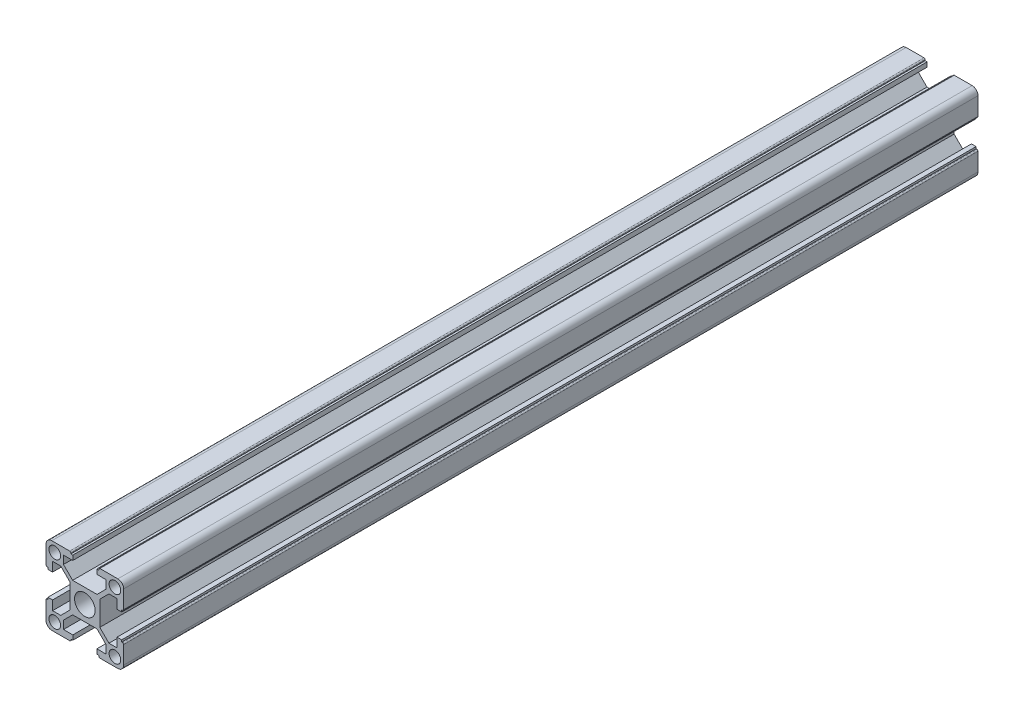
SolidWorks part; units mm, degrees
ref_plane "前视基准面" through (0, 0, 0) normal (0, 0, 1) x (1, 0, 0)
ref_plane "上视基准面" through (0, 0, 0) normal (0, 1, 0) x (1, 0, 0)
ref_plane "右视基准面" through (0, 0, 0) normal (1, 0, 0) x (0, 0, -1)
sketch "草图1" plane through (0, 0, 0) normal (0, 0, 1) x (1, 0, 0)
  line L0 (-7.75, 0) -> (0, 0) construction
  line L1 (7.75, -7.75) -> (-7.75, -7.75) construction
  line L2 (7.75, -7.75) -> (7.75, 7.75) construction
  line L3 (7.75, 7.75) -> (-7.75, 7.75) construction
  line L4 (-7.75, -7.75) -> (-7.75, 7.75) construction
  line L5 (7.75, -7.75) -> (-7.75, 7.75) construction
  line L6 (7.75, 7.75) -> (-7.75, -7.75) construction
  line L7 (0, 0) -> (0, 7.75) construction
  line L8 (3.1429, 3.85) -> (-3.1429, 3.85)
  line L9 (-3.1429, 3.85) -> (-5.5, 6.2071)
  line L10 (-5.5, 6.2071) -> (-5.5, 8.3)
  line L11 (-5.5, 8.3) -> (-3.1, 8.3)
  line L12 (-3.1, 8.3) -> (-3.1, 9.5)
  line L13 (-3.1, 9.5) -> (-3.6, 9.5)
  line L14 (-3.6, 9.5) -> (-3.6, 9.7)
  line L15 (-3.9, 10) -> (-8.5, 10)
  line L16 (-3.85, -3.1429) -> (-3.85, 3.1429)
  line L17 (-3.85, 3.1429) -> (-6.2071, 5.5)
  line L18 (-6.2071, 5.5) -> (-8.3, 5.5)
  line L19 (-8.3, 5.5) -> (-8.3, 3.1)
  line L20 (-9.5, 3.1) -> (-9.5, 3.6)
  line L21 (-8.3, 3.1) -> (-9.5, 3.1)
  line L22 (-9.5, 3.6) -> (-9.7, 3.6)
  line L23 (-10, 3.9) -> (-10, 8.5)
  line L24 (5.5, 8.3) -> (3.1, 8.3)
  line L25 (3.6, 9.5) -> (3.6, 9.7)
  line L26 (3.1, 9.5) -> (3.6, 9.5)
  line L27 (3.1, 8.3) -> (3.1, 9.5)
  line L28 (5.5, 6.2071) -> (5.5, 8.3)
  line L29 (3.1429, 3.85) -> (5.5, 6.2071)
  line L30 (3.85, -3.1429) -> (3.85, 3.1429)
  line L31 (3.85, 3.1429) -> (6.2071, 5.5)
  line L32 (9.5, 3.6) -> (9.7, 3.6)
  line L33 (8.3, 3.1) -> (9.5, 3.1)
  line L34 (9.5, 3.1) -> (9.5, 3.6)
  line L35 (8.3, 5.5) -> (8.3, 3.1)
  line L36 (6.2071, 5.5) -> (8.3, 5.5)
  line L37 (10, 3.9) -> (10, 8.5)
  line L38 (3.9, 10) -> (8.5, 10)
  line L39 (-9.5, -3.6) -> (-9.7, -3.6)
  line L40 (-8.3, -3.1) -> (-9.5, -3.1)
  line L41 (-9.5, -3.1) -> (-9.5, -3.6)
  line L42 (-8.3, -5.5) -> (-8.3, -3.1)
  line L43 (-6.2071, -5.5) -> (-8.3, -5.5)
  line L44 (-3.85, -3.1429) -> (-6.2071, -5.5)
  line L45 (-3.1429, -3.85) -> (-5.5, -6.2071)
  line L46 (-5.5, -6.2071) -> (-5.5, -8.3)
  line L47 (-3.6, -9.5) -> (-3.6, -9.7)
  line L48 (-3.1, -9.5) -> (-3.6, -9.5)
  line L49 (-3.1, -8.3) -> (-3.1, -9.5)
  line L50 (-5.5, -8.3) -> (-3.1, -8.3)
  line L51 (5.5, -6.2071) -> (5.5, -8.3)
  line L52 (3.1, -8.3) -> (3.1, -9.5)
  line L53 (3.1, -9.5) -> (3.6, -9.5)
  line L54 (3.6, -9.5) -> (3.6, -9.7)
  line L55 (5.5, -8.3) -> (3.1, -8.3)
  line L56 (3.1429, -3.85) -> (5.5, -6.2071)
  line L57 (3.1429, -3.85) -> (-3.1429, -3.85)
  line L58 (3.85, -3.1429) -> (6.2071, -5.5)
  line L59 (6.2071, -5.5) -> (8.3, -5.5)
  line L60 (8.3, -5.5) -> (8.3, -3.1)
  line L61 (9.5, -3.1) -> (9.5, -3.6)
  line L62 (8.3, -3.1) -> (9.5, -3.1)
  line L63 (9.5, -3.6) -> (9.7, -3.6)
  line L64 (3.9, -10) -> (8.5, -10)
  line L65 (10, -3.9) -> (10, -8.5)
  line L66 (-10, -3.9) -> (-10, -8.5)
  line L67 (-3.9, -10) -> (-8.5, -10)
  circle A0 centre (0, 0) radius 2.65
  circle A1 centre (-7.75, 7.75) radius 1.5
  circle A2 centre (7.75, 7.75) radius 1.5
  circle A3 centre (7.75, -7.75) radius 1.5
  circle A4 centre (-7.75, -7.75) radius 1.5
  arc A5 (-10, -8.5) -> (-8.5, -10) centre (-8.5, -8.5) ccw
  arc A6 (8.5, -10) -> (10, -8.5) centre (8.5, -8.5) ccw
  arc A7 (10, 8.5) -> (8.5, 10) centre (8.5, 8.5) ccw
  arc A8 (-8.5, 10) -> (-10, 8.5) centre (-8.5, 8.5) ccw
  arc A9 (3.6, -9.7) -> (3.9, -10) centre (3.9, -9.7) ccw
  arc A10 (-3.6, -9.7) -> (-3.9, -10) centre (-3.9, -9.7) cw
  arc A11 (-9.7, -3.6) -> (-10, -3.9) centre (-9.7, -3.9) ccw
  arc A12 (9.7, -3.6) -> (10, -3.9) centre (9.7, -3.9) cw
  arc A13 (9.7, 3.6) -> (10, 3.9) centre (9.7, 3.9) ccw
  arc A14 (-9.7, 3.6) -> (-10, 3.9) centre (-9.7, 3.9) cw
  arc A15 (3.6, 9.7) -> (3.9, 10) centre (3.9, 9.7) cw
  arc A16 (-3.6, 9.7) -> (-3.9, 10) centre (-3.9, 9.7) ccw
  point P46 (0, 3.85)
  point P56 (-3.85, 0)
  point P78 (3.85, 0)
  point P87 (-10, -10)
  point P90 (10, -10)
  point P93 (10, 10)
  point P96 (-10, 10)
  point P99 (3.6, -10)
  point P102 (-3.6, -10)
  point P105 (-10, -3.6)
  point P108 (10, -3.6)
  point P111 (10, 3.6)
  point P114 (-10, 3.6)
  point P117 (3.6, 10)
  point P120 (-3.6, 10)
  dimension "D1" = 5.3
  dimension "D2" = 3
  dimension "D11" = 1.5
  dimension "D12" = 2.25
  dimension "D13" = 0.3
  dimension "D3" = 7.7
  dimension "D4" = 6.2
  dimension "D5" = 1.7
  dimension "D6" = 1.2
  dimension "D7" = 20
  dimension "D8" = 7.2
  dimension "D9" = 11
  dimension "D10" = 1
extrude "凸台-拉伸1" add sketch "草图1" along normal mid plane 220
sketch "草图4" plane through (3.85, 0, 0) normal (1, 0, 0) x (0, 0, -1)
  line L0 (100, 0) -> (-100, 0) construction
  line L1 (-110, -3.1429) -> (-110, 3.1429) construction
  line L2 (0, 0) -> (0, -10) construction
  line L3 (-110, -10) -> (110, -10) construction
  circle A0 centre (-100, 0) radius 2
  circle A1 centre (100, 0) radius 2
  circle A4 centre (-45, 0) radius 2
  circle A6 centre (-80, 0) radius 2
  circle A7 centre (45, 0) radius 2
  circle A8 centre (80, 0) radius 2
  point P4 (0, 0)
  dimension "D1" = 4
  dimension "D2" = 10
  dimension "D3" = 20
  dimension "D4" = 35
extrude "切除-拉伸3" cut sketch "草图4" against normal through all
